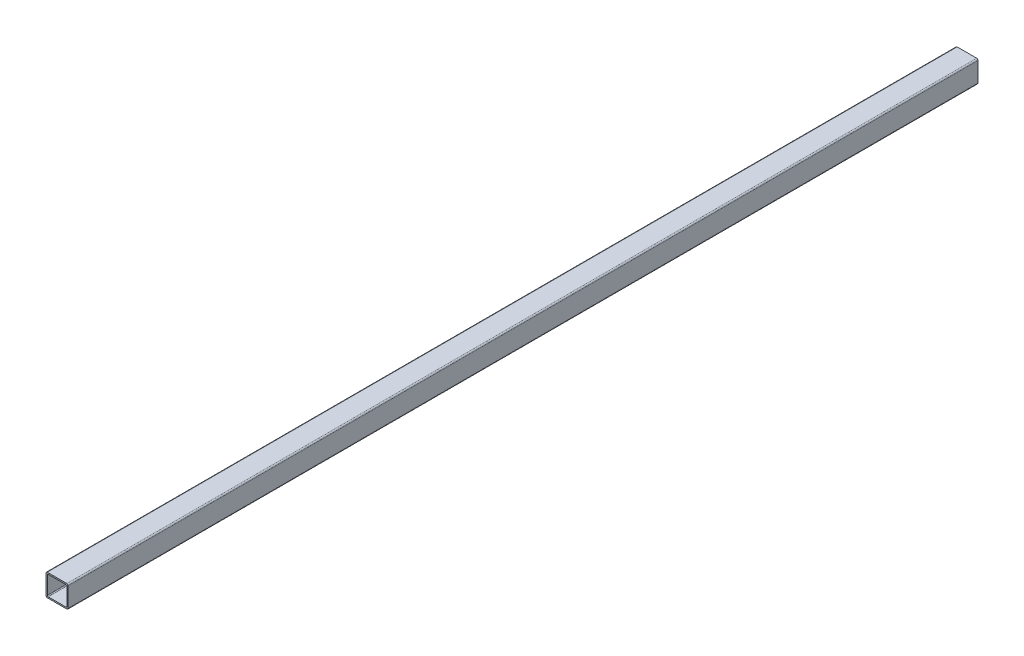
SolidWorks part; units mm, degrees
material "AISI 1020"
ref_plane "Спереди" through (0, 0, 0) normal (0, 0, 1) x (1, 0, 0)
ref_plane "Сверху" through (0, 0, 0) normal (0, 1, 0) x (1, 0, 0)
ref_plane "Справа" through (0, 0, 0) normal (1, 0, 0) x (0, 0, -1)
sketch "Эскиз1" plane through (0, 0, 0) normal (0, 0, 1) x (1, 0, 0)
  line B0 (-22, 25) -> (22, 25)
  line B1 (-25, 22) -> (-25, -22)
  line B2 (-22, -25) -> (22, -25)
  line B3 (25, 22) -> (25, -22)
  line B4 (-20, 22) -> (20, 22)
  line B5 (-22, 20) -> (-22, -20)
  line B6 (-20, -22) -> (20, -22)
  line B7 (22, 20) -> (22, -20)
  arc B8 (-25, -22) -> (-22, -25) centre (-22, -22) ccw
  arc B9 (22, -25) -> (25, -22) centre (22, -22) ccw
  arc B10 (22, 25) -> (25, 22) centre (22, 22) cw
  arc B11 (-22, 25) -> (-25, 22) centre (-22, 22) ccw
  arc B12 (-22, -20) -> (-20, -22) centre (-20, -20) ccw
  arc B13 (20, -22) -> (22, -20) centre (20, -20) ccw
  arc B14 (20, 22) -> (22, 20) centre (20, 20) cw
  arc B15 (-20, 22) -> (-22, 20) centre (-20, 20) ccw
sketch_block_instance "Труба профильная 50х50х3-1"
sketch_block "Труба профильная 50х50х3" parameters "D3"=3, "D4"=2, "D1"=50, "D2"=3
extrude "Бобышка-Вытянуть1" add sketch "Эскиз1" against normal up to vertex (2054.3307 mm away)
sketch "Эскиз2" plane through (25, 0, 0) normal (1, 0, 0) x (0, 0, -1)
  line L0 (2054.3307, -22) -> (2025.4631, 25)
  line L1 (545.6311, 2588.1443) -> (521.4311, 2630.0599) construction
  line L2 (2025.4631, 25) -> (2054.3307, 25)
  line L3 (2054.3307, 25) -> (2054.3307, -22)
  line L4 (2054.3307, -22) -> (2054.3307, 22) construction
  line L5 (2054.3307, 25) -> (0, 25) construction
  line L7 (2054.3307, -22) -> (2054.3307, 22) construction
  line L8 (2054.3307, -22) -> (0, -22) construction
